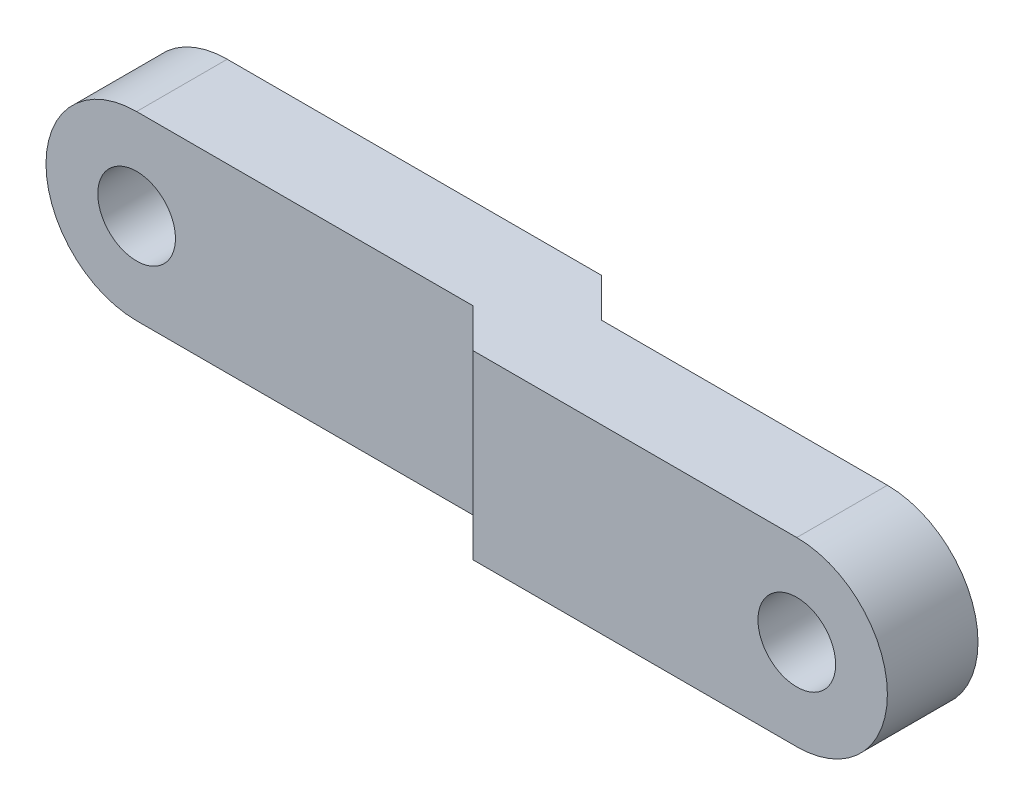
SolidWorks part; units mm, degrees
ref_plane "Front Plane" through (0, 0, 0) normal (0, 0, 1) x (1, 0, 0)
ref_plane "Top Plane" through (0, 0, 0) normal (0, 1, 0) x (1, 0, 0)
ref_plane "Right Plane" through (0, 0, 0) normal (1, 0, 0) x (0, 0, -1)
sketch "Sketch1" plane through (0, 0, 0) normal (0, 0, 1) x (1, 0, 0)
  line L0 (0, 0) -> (27, 0)
  line L5 (0, -7) -> (27, -7)
  arc A8 (27, 0) -> (27, -7) centre (27, -3.5) cw
  arc A9 (0, -7) -> (0, 0) centre (0, -3.5) cw
  circle A10 centre (0, -3.5) radius 1.5
  circle A11 centre (27, -3.5) radius 1.5
  dimension "D1" = 3
  dimension "D2" = 3
  dimension "D3" = 2
  dimension "D4" = 27
  dimension "D5" = 2
extrude "Boss-Extrude1" add sketch "Sketch1" along normal blind 5
sketch "Sketch2" plane through (0, 0, 0) normal (0, 1, 0) x (1, 0, 0)
  line L0 (30.5, -5) -> (14.5, -5)
  line L1 (27, -5) -> (0, -5) construction
  line L2 (14.5, -5) -> (13, -3.5)
  line L3 (13, -3.5) -> (-3.5, -3.5)
  line L4 (-3.5, 0) -> (-3.5, -5) construction
  line L5 (-3.5, -3.5) -> (-3.5, 0)
  line L6 (-3.5, 0) -> (14.4497, 0)
  line L7 (27, 0) -> (0, 0) construction
  line L8 (14.4497, 0) -> (15.9497, -1.5)
  line L9 (15.9497, -1.5) -> (30.5, -1.5)
  line L11 (30.5, -1.5) -> (30.5, -5)
  line L12 (14.5, -5) -> (-3.5, -5)
  line L13 (-3.5, -5) -> (-3.5, -3.5)
  line L14 (14.4497, 0) -> (30.5, 0)
  line L15 (30.5, 0) -> (30.5, -1.5)
  line M9 (27, 0) -> (0, 0)
  line M10 (0, 0) -> (0, -5)
  line M11 (0, -5) -> (27, -5)
  line M12 (27, -5) -> (27, 0)
  dimension "D1" = 3.5
  dimension "D2" = 3.5
  dimension "D3" = 135
  dimension "D4" = 3.5
  dimension "D5" = 16
extrude "Cut-Extrude1" cut sketch "Sketch2" against normal through all contours L2 L3 M10 M11 | L8 L9 M12 M9 | L13 L12 L3 M10 | L15 L14 L9 M12
